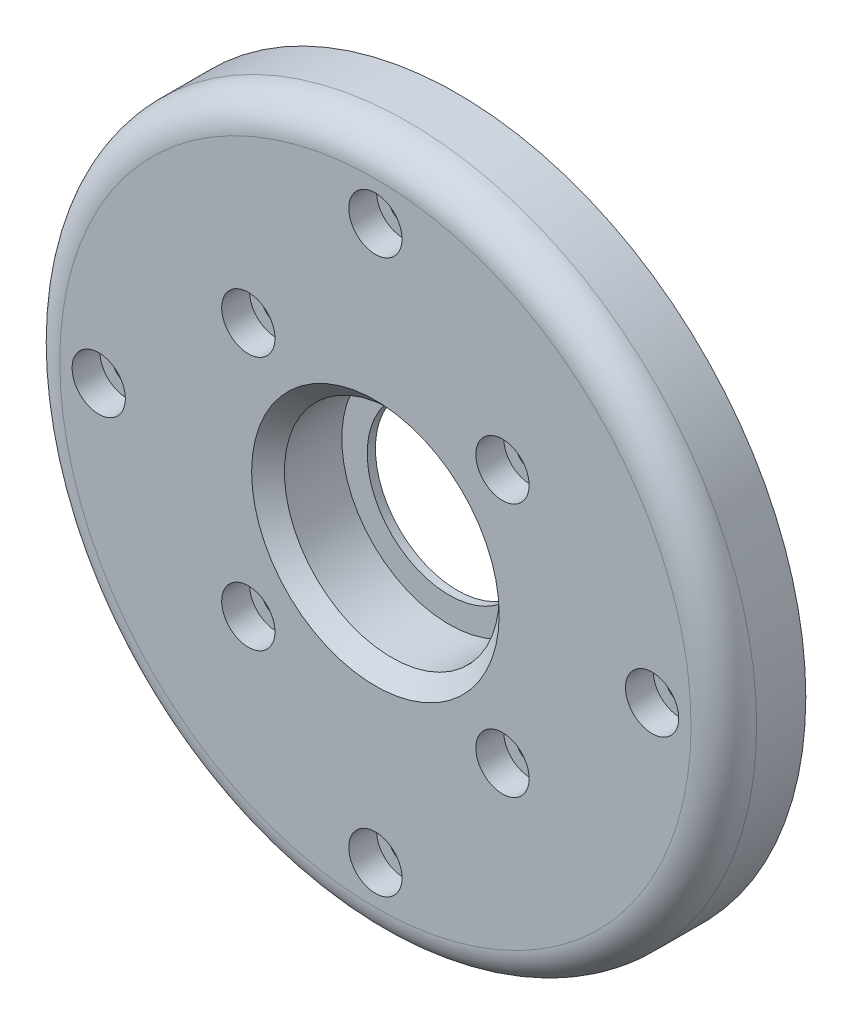
SolidWorks part; units mm, degrees
ref_plane "Ebene vorne" through (0, 0, 0) normal (0, 0, 1) x (1, 0, 0)
ref_plane "Ebene oben" through (0, 0, 0) normal (0, 1, 0) x (1, 0, 0)
ref_plane "Ebene rechts" through (0, 0, 0) normal (1, 0, 0) x (0, 0, -1)
sketch "Skizze3" plane through (0, 0, 0) normal (0, 0, 1) x (1, 0, 0)
  circle A0 centre (0, 0) radius 42.5
  dimension "D1" = 85
extrude "Aufsatz-Linear austragen1" add sketch "Skizze3" along normal blind 10
sketch "Skizze4" plane through (0, 0, 10) normal (0, 0, 1) x (1, 0, 0)
  circle A1 centre (0, 0) radius 10
  dimension "D1" = 20
extrude "Schnitt-Linear austragen1" cut sketch "Skizze4" against normal up to surface (10 mm away) up to face at (42.5, 0, 0)
sketch "Skizze5" plane through (0, 0, 10) normal (0, 0, 1) x (1, 0, 0)
  line L0 (0, 0) -> (-33.75, 0) construction
  line L1 (-15.5, -15.5) -> (15.5, -15.5) construction
  line L2 (-15.5, -15.5) -> (-15.5, 15.5) construction
  line L3 (-15.5, 15.5) -> (15.5, 15.5) construction
  line L4 (15.5, -15.5) -> (15.5, 15.5) construction
  line L5 (-15.5, -15.5) -> (15.5, 15.5) construction
  line L6 (-15.5, 15.5) -> (15.5, -15.5) construction
  circle A0 centre (-15.5, 15.5) radius 3.25
  circle A1 centre (-33.75, 0) radius 3.25
  point P0 (0, 0)
  dimension "D3" = 6.5
  dimension "D1" = 31
  dimension "D2" = 31
  dimension "D4" = 33.75
extrude "Schnitt-Linear austragen3" cut sketch "Skizze5" against normal blind 3.4
sketch "Skizze6" plane through (0, 0, 6.6) normal (0, 0, 1) x (1, 0, 0)
  circle A0 centre (-15.5, 15.5) radius 1.7
  circle A1 centre (-33.75, 0) radius 1.7
  dimension "D1" = 3.4
extrude "Schnitt-Linear austragen4" cut sketch "Skizze6" against normal up to surface (6.6 mm away) up to face at (10, 0, 0)
pattern_circular "Kreismuster1" count 4 over 360 about axis through (0, 0, 0) along (0, 0, 1) of "Schnitt-Linear austragen3", "Schnitt-Linear austragen4"
sketch "Skizze7" plane through (0, 0, 10) normal (0, 0, 1) x (1, 0, 0)
  circle A0 centre (0, 0) radius 13.1
  dimension "D1" = 26.2
extrude "Schnitt-Linear austragen5" cut sketch "Skizze7" against normal blind 9
fillet "Verrundung1" radius 4 1 edges at (42.5, 0, 10)
chamfer "Fase1" distance 2 angle 45 1 edges at (13.1, 0, 10)
